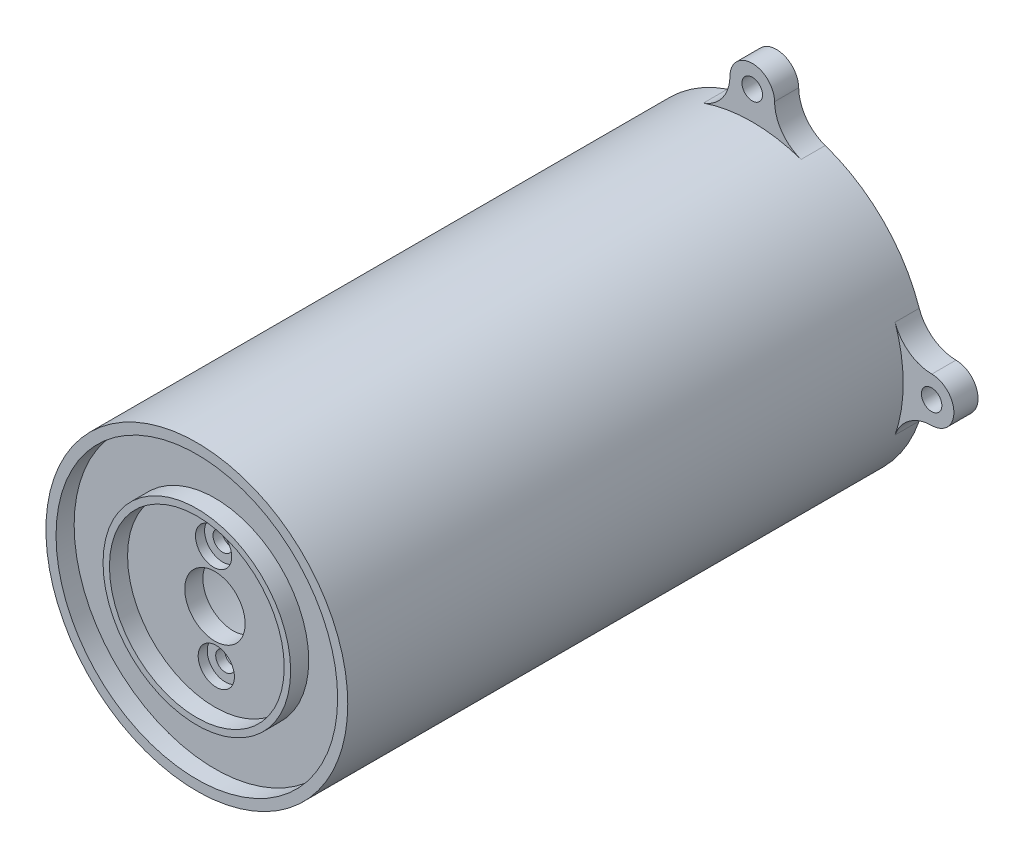
SolidWorks part; units mm, degrees
material "PLA"
ref_plane "Front Plane" through (0, 0, 0) normal (1, 0, 0) x (0, 1, 0)
ref_plane "Top Plane" through (0, 0, 0) normal (0, 0, 1) x (0, 1, 0)
ref_plane "Right Plane" through (0, 0, 0) normal (0, 1, 0) x (-1, 0, 0)
sketch "Sketch1" plane through (0, 0, 0) normal (0, 0, 1) x (0, 1, 0)
  circle A0 centre (0, 0) radius 24
  circle A1 centre (0, 0) radius 25
  dimension "D1" = 48
  dimension "D2" = 50
extrude "Boss-Extrude1" add sketch "Sketch1" along normal blind 90
sketch "Sketch2" plane through (90, 0, 90) normal (0, 0, 1) x (0, 1, 0)
  circle A0 centre (0, 90) radius 25
  circle A1 centre (0, 90) radius 5
  circle A4 centre (-8.4971, 89.7779) radius 1.6
  circle A5 centre (8.4971, 90.2221) radius 1.6
  dimension "D2" = 10
extrude "Boss-Extrude2" add sketch "Sketch2" along normal blind 3
sketch "Sketch3" plane through (0, 0, 93) normal (0, 0, 1) x (1, 0, 0)
  circle A0 centre (-0.2221, 8.4971) radius 3
  circle A1 centre (0.2221, -8.4971) radius 3
  dimension "D1" = 6
extrude "Cut-Extrude1" cut sketch "Sketch3" against normal blind 1.5
sketch "Sketch4" plane through (0, 0, 0) normal (0, 0, -1) x (1, 0, 0)
  line L0 (0, 41.6777) -> (0, -29.3467) construction
  circle A30 centre (0, 0) radius 25 construction
  arc A31 (-8.0884, 23.6554) -> (-23.6554, 8.0884) centre (0, 0) ccw
  circle A32 centre (0, 29.7067) radius 1.7
  arc A33 (3.6916, 29.7426) -> (-3.6916, 29.7426) centre (0, 29.7067) ccw
  arc A34 (3.6916, 29.7426) -> (8.0884, 23.6554) centre (10.1913, 29.8058) ccw
  arc A35 (-3.6916, 29.7426) -> (-8.0884, 23.6554) centre (-10.1913, 29.8058) cw
  circle A36 centre (29.7067, 0) radius 1.7
  arc A37 (29.7426, -3.6916) -> (29.7426, 3.6916) centre (29.7067, 0) ccw
  arc A38 (29.7426, -3.6916) -> (23.6554, -8.0884) centre (29.8058, -10.1913) ccw
  arc A39 (29.7426, 3.6916) -> (23.6554, 8.0884) centre (29.8058, 10.1913) cw
  circle A40 centre (0, -29.7067) radius 1.7
  arc A41 (-3.6916, -29.7426) -> (3.6916, -29.7426) centre (0, -29.7067) ccw
  arc A42 (-3.6916, -29.7426) -> (-8.0884, -23.6554) centre (-10.1913, -29.8058) ccw
  arc A43 (3.6916, -29.7426) -> (8.0884, -23.6554) centre (10.1913, -29.8058) cw
  circle A44 centre (-29.7067, 0) radius 1.7
  arc A45 (-29.7426, 3.6916) -> (-29.7426, -3.6916) centre (-29.7067, 0) ccw
  arc A46 (-29.7426, 3.6916) -> (-23.6554, 8.0884) centre (-29.8058, 10.1913) ccw
  arc A47 (-29.7426, -3.6916) -> (-23.6554, -8.0884) centre (-29.8058, -10.1913) cw
  arc A48 (-23.6554, -8.0884) -> (-8.0884, -23.6554) centre (0, 0) ccw
  arc A49 (8.0884, -23.6554) -> (23.6554, -8.0884) centre (0, 0) ccw
  arc A50 (23.6554, 8.0884) -> (8.0884, 23.6554) centre (0, 0) ccw
  circle A51 centre (0, 0) radius 24 construction
  circle A52 centre (0, 0) radius 24
  point P39 (0, 0)
  dimension "D1" = 4
extrude "Boss-Extrude3" add sketch "Sketch4" against normal blind 4
sketch "Sketch5" plane through (0, 0, 93) normal (0, 0, 1) x (1, 0, 0)
  circle A0 centre (0, 0) radius 25
  circle A1 centre (0, 0) radius 23.3221
  circle A2 centre (0, 0) radius 15.5383
  circle A3 centre (0, 0) radius 14.4752
  circle M4 centre (0, 0) radius 25
extrude "Boss-Extrude4" add sketch "Sketch5" along normal blind 3 contours A1 M4 | A2 A3
